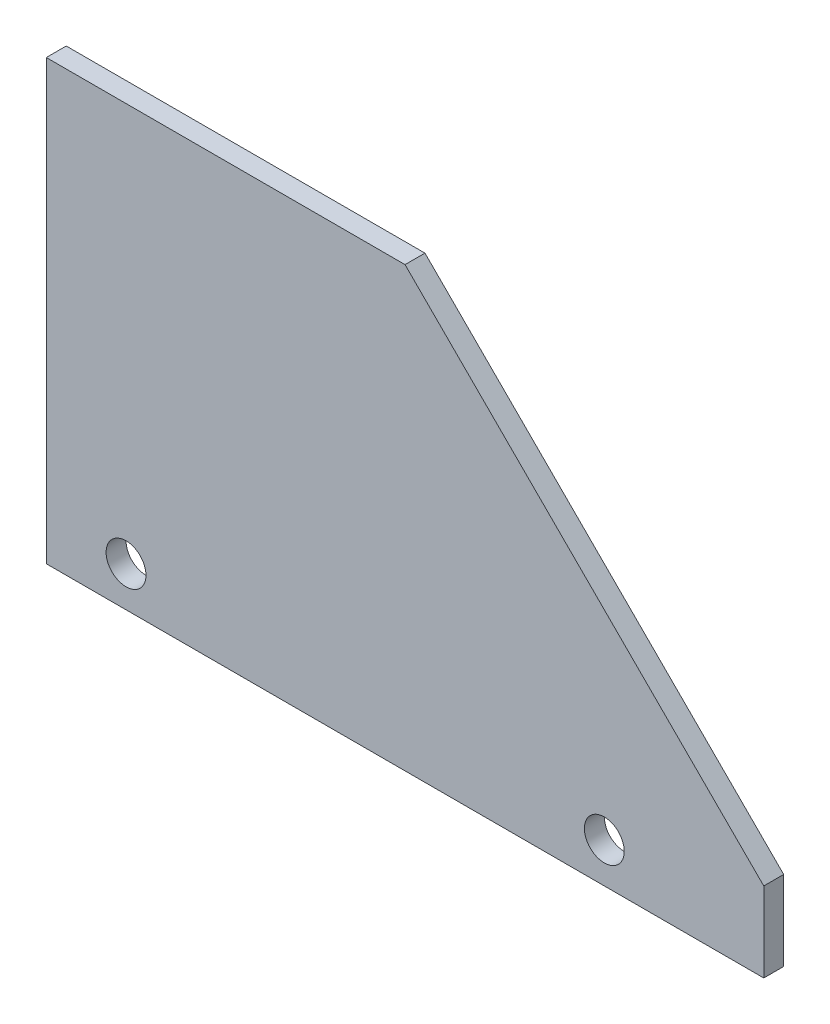
SolidWorks part; units mm, degrees
ref_plane "Front Plane" through (0, 0, 0) normal (0, 0, 1) x (1, 0, 0)
ref_plane "Top Plane" through (0, 0, 0) normal (0, 1, 0) x (1, 0, 0)
ref_plane "Right Plane" through (0, 0, 0) normal (1, 0, 0) x (0, 0, -1)
sketch "Sketch1" plane through (0, 0, 0) normal (0, 0, 1) x (1, 0, 0)
  line L0 (0, 0) -> (0, 34.925)
  line L1 (0, 34.925) -> (34.925, 34.925)
  line L2 (34.925, 34.925) -> (63.5, 6.35)
  line L3 (63.5, 6.35) -> (63.5, 0)
  line L4 (63.5, 0) -> (0, 0)
  dimension "D1" = 6.35
  dimension "D2" = 34.925
  dimension "D3" = 63.5
  dimension "D4" = 135
extrude "Boss-Extrude1" add sketch "Sketch1" along normal blind 1.5875
sketch "Sketch2" plane through (0, 0, 1.5875) normal (0, 0, 1) x (1, 0, 0)
  line L0 (0, 0) -> (63.5, 0) construction
  line L1 (0, 34.925) -> (0, 0) construction
  circle A0 centre (12.7, 3.175) radius 1.5875
  dimension "D1" = 3.175
  dimension "D2" = 3.175
  dimension "D3" = 12.7
extrude "Cut-Extrude1" cut sketch "Sketch2" against normal blind 2.54
pattern_linear "LPattern2" count 2 spacing 38.1 along (1, 0, 0) of "Cut-Extrude1"
sketch "Sketch3" plane through (0, 0, 1.5875) normal (0, 0, 1) x (1, 0, 0)
  line L0 (34.925, 34.925) -> (0, 34.925) construction
  line L1 (0, 0) -> (6.35, 0)
  line L2 (0, 0) -> (0, 34.925)
  line L3 (0, 34.925) -> (6.35, 34.925)
  line L4 (6.35, 0) -> (6.35, 34.925)
  dimension "D1" = 6.35
extrude "Cut-Extrude2" cut sketch "Sketch3" against normal blind 2.54
